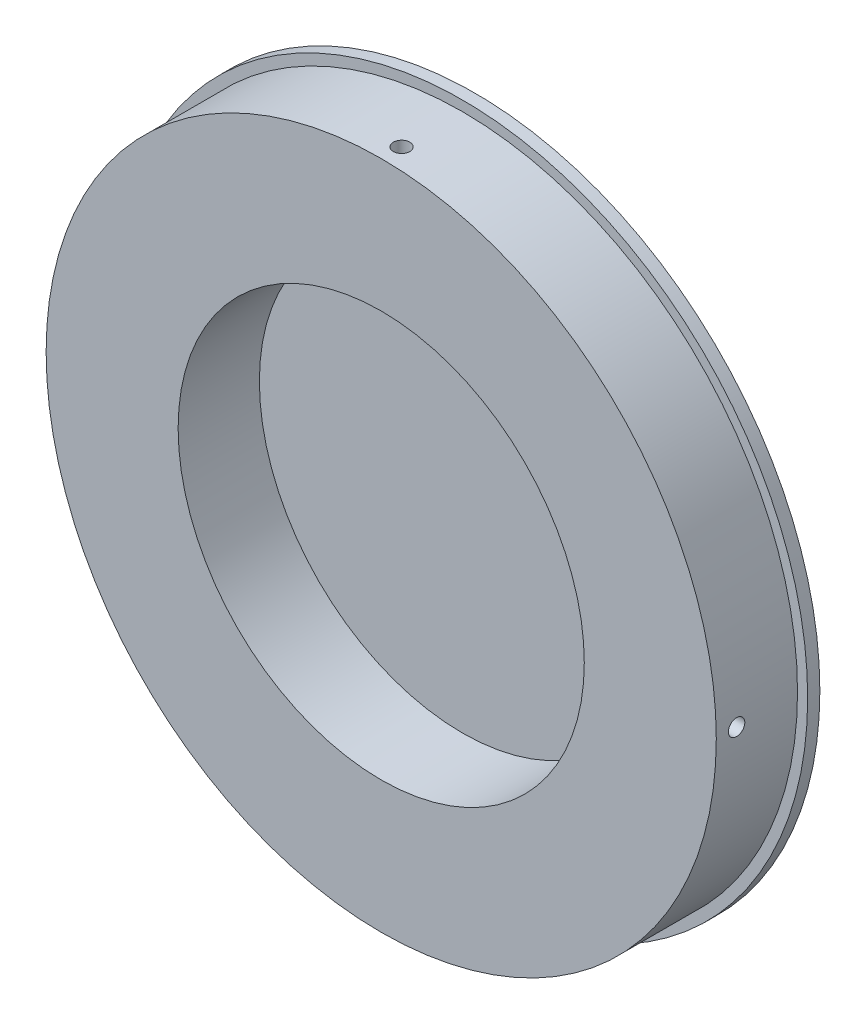
SolidWorks part; units mm, degrees
ref_plane "Front Plane" through (0, 0, 0) normal (0, 0, 1) x (1, 0, 0)
ref_plane "Top Plane" through (0, 0, 0) normal (0, 1, 0) x (1, 0, 0)
ref_plane "Right Plane" through (0, 0, 0) normal (1, 0, 0) x (0, 0, -1)
sketch "Sketch1" plane through (0, 0, 0) normal (0, 0, 1) x (1, 0, 0)
  circle A0 centre (0, 0) radius 85
ref_plane "Plane1" through (0, 0, 3) normal (0, 0, 1) x (1, 0, 0)
sketch "Sketch2" plane through (0, 0, 3) normal (0, 0, 1) x (1, 0, 0)
  circle A0 centre (0, 0) radius 82.5
extrude "Boss-Extrude2" add sketch "Sketch1" along normal blind 3 contours A0
extrude "Boss-Extrude3" add sketch "Sketch2" along normal blind 20 contours A0
ref_plane "Plane2" through (0, 0, 23) normal (0, 0, 1) x (1, 0, 0)
sketch "Sketch3" plane through (0, 0, 23) normal (0, 0, 1) x (1, 0, 0)
  circle A0 centre (0, 0) radius 50
extrude "Cut-Extrude1" cut sketch "Sketch3" against normal blind 20
ref_plane "Plane3" through (0, 82.5, 0) normal (0, -1, 0) x (-1, 0, 0)
sketch "Sketch9" plane through (0, 82.5, 0) normal (0, -1, 0) x (-1, 0, 0)
  line L0 (0, -3) -> (0, -18)
  line L1 (-93.5, -3) -> (93.5, -3) construction
  circle A0 centre (0, -18) radius 2.0193
extrude "Cut-Extrude5" cut sketch "Sketch9" along normal blind 19.05 contours A0
ref_plane "Plane4" through (0, -82.5, 0) normal (0, 1, 0) x (1, 0, 0)
ref_plane "Plane5" through (82.5, 0, 0) normal (1, 0, 0) x (0, 0, -1)
ref_plane "Plane6" through (-82.5, 0, 0) normal (1, 0, 0) x (0, 0, -1)
sketch "Sketch10" plane through (0, -82.5, 0) normal (0, 1, 0) x (1, 0, 0)
  line L0 (0, -3) -> (0, -18)
  line L1 (-93.5, -3) -> (93.5, -3) construction
  circle A0 centre (0, -18) radius 2.0193
extrude "Cut-Extrude6" cut sketch "Sketch10" along normal blind 19.05 contours A0
sketch "Sketch11" plane through (82.5, 0, 0) normal (1, 0, 0) x (0, 0, -1)
  line L0 (-3, 0) -> (-18, 0)
  line L1 (-3, 93.5) -> (-3, -93.5) construction
  circle A0 centre (-18, 0) radius 2.0193
extrude "Cut-Extrude7" cut sketch "Sketch11" against normal blind 19.05 contours A0
sketch "Sketch12" plane through (-82.5, 0, 0) normal (1, 0, 0) x (0, 0, -1)
  line L0 (-3, 0) -> (-18, 0)
  line L1 (-3, 93.5) -> (-3, -93.5) construction
  circle A0 centre (-18, 0) radius 2.0193
extrude "Cut-Extrude8" cut sketch "Sketch12" along normal blind 19.05 contours A0
